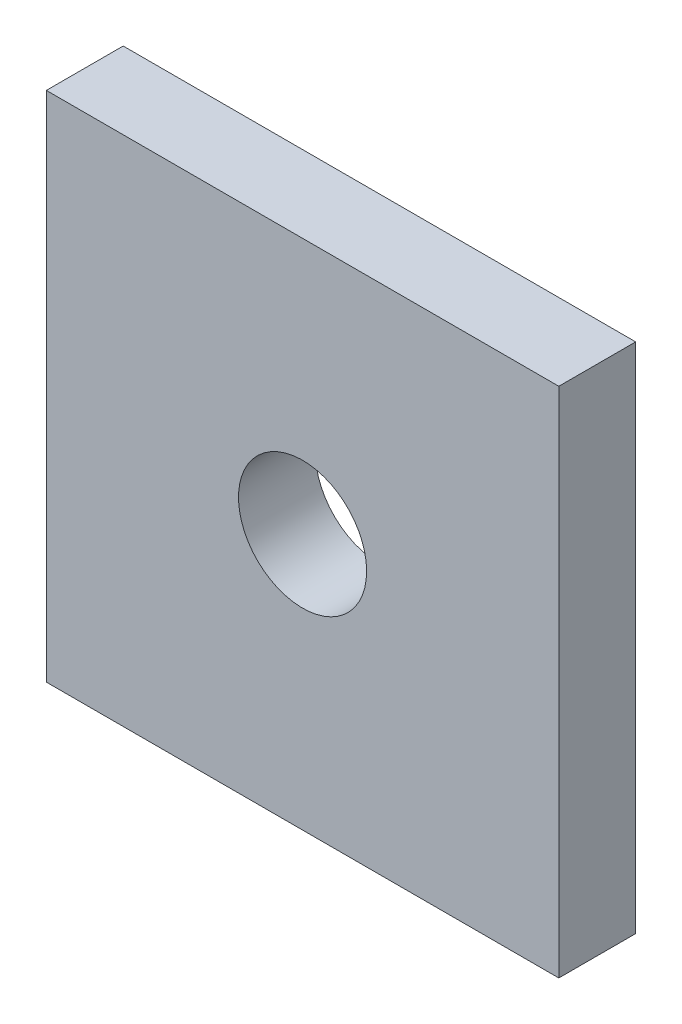
SolidWorks part; units mm, degrees
material "6063-T5"
ref_plane "Plano frontal" through (0, 0, 0) normal (0, 0, 1) x (1, 0, 0)
ref_plane "Plano superior" through (0, 0, 0) normal (0, 1, 0) x (1, 0, 0)
ref_plane "Plano direito" through (0, 0, 0) normal (1, 0, 0) x (0, 0, -1)
sketch "Esboço1" plane through (0, 0, 0) normal (0, 0, 1) x (1, 0, 0)
  line L1 (10, 10) -> (-10, 10)
  line L2 (10, 10) -> (10, -10)
  line L3 (10, -10) -> (-10, -10)
  line L4 (-10, 10) -> (-10, -10)
  line L5 (10, 10) -> (-10, -10) construction
  line L6 (10, -10) -> (-10, 10) construction
  circle A0 centre (0, 0) radius 2.5
  dimension "D1" = 5
  dimension "D2" = 20
  dimension "D3" = 20
extrude "Ressalto-extrusão1" add sketch "Esboço1" along normal blind 3
